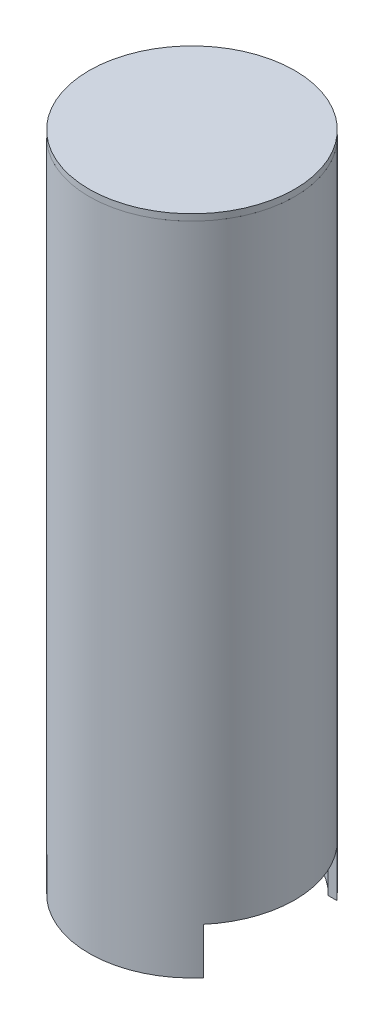
SolidWorks part; units mm, degrees
other "Glass Body"
ref_plane "Front Plane" through (0, 0, 0) normal (0, 0, 1) x (1, 0, 0)
ref_plane "Top Plane" through (0, 0, 0) normal (0, 1, 0) x (1, 0, 0)
ref_plane "Right Plane" through (0, 0, 0) normal (1, 0, 0) x (0, 0, -1)
sketch "Sketch1" plane through (0, 0, 0) normal (0, 1, 0) x (1, 0, 0)
  circle A0 centre (0, 0) radius 50.8
  dimension "D1" = 101.6
extrude "Base" add sketch "Sketch1" along normal blind 323.85
sketch "Sketch3" plane through (0, 0, 0) normal (0, -1, 0) x (-1, 0, 0)
  circle A0 centre (0, 0) radius 47.625
  dimension "D1" = 95.25
extrude "Bottom Cut" cut sketch "Sketch3" against normal blind 25.4
sketch "Sketch4" plane through (0, 0, 0) normal (1, 0, 0) x (0, 0, -1)
  line L0 (33.02, 0) -> (-33.02, 0)
  line L1 (-33.02, 0) -> (-33.02, 22.86)
  line L2 (-33.02, 22.86) -> (33.02, 22.86)
  line L3 (33.02, 22.86) -> (33.02, 0)
  point P4 (0, 0)
  dimension "D1" = 22.86
  dimension "D2" = 66.04
extrude "Bottom Side" cut sketch "Sketch4" along normal blind 58.42
ref_plane "Inside" through (0, 26.67, 0) normal (0, 1, 0) x (1, 0, 0)
sketch "Sketch5" plane through (0, 26.67, 0) normal (0, 1, 0) x (1, 0, 0)
  circle A0 centre (0, 0) radius 47.625
  dimension "D1" = 95.25
extrude "Inside Cut" cut sketch "Sketch5" along normal through all
sketch "Sketch6" plane through (0, 26.67, 0) normal (0, 1, 0) x (1, 0, 0)
  circle A0 centre (0, 0) radius 3.175
  dimension "D1" = 6.35
extrude "Red on bottom" add sketch "Sketch6" along normal blind 1.905 separate body
sketch "Sketch7" plane through (0, 28.575, 0) normal (0, 1, 0) x (1, 0, 0)
  circle A0 centre (0, 0) radius 1.905
  dimension "D1" = 3.81
extrude "Black on red" add sketch "Sketch7" along normal blind 0.635 separate body
sketch "Sketch8" plane through (0, 323.85, 0) normal (0, 1, 0) x (1, 0, 0)
  circle A0 centre (0, 0) radius 46.99
  dimension "D1" = 93.98
extrude "Cap top" add sketch "Sketch8" against normal blind 5.715 separate body
sketch "Sketch9" plane through (0, 323.85, 0) normal (0, 1, 0) x (1, 0, 0)
  circle A0 centre (0, 0) radius 50.8
  dimension "D1" = 101.6
extrude "cap bottom portion" add sketch "Sketch9" along normal blind 3.175 separate body
combine bodies "Cap Body" operation type add bodies to combine 107 108
combine bodies "Connector Body" operation type add bodies to combine 105 106
sketch "Sketch11" plane through (0, 25.4, 0) normal (0, -1, 0) x (1, 0, 0)
  circle A0 centre (0, 0) radius 1.27
  dimension "D1" = 2.54
extrude "Connection cut" cut sketch "Sketch11" against normal blind 1.778
